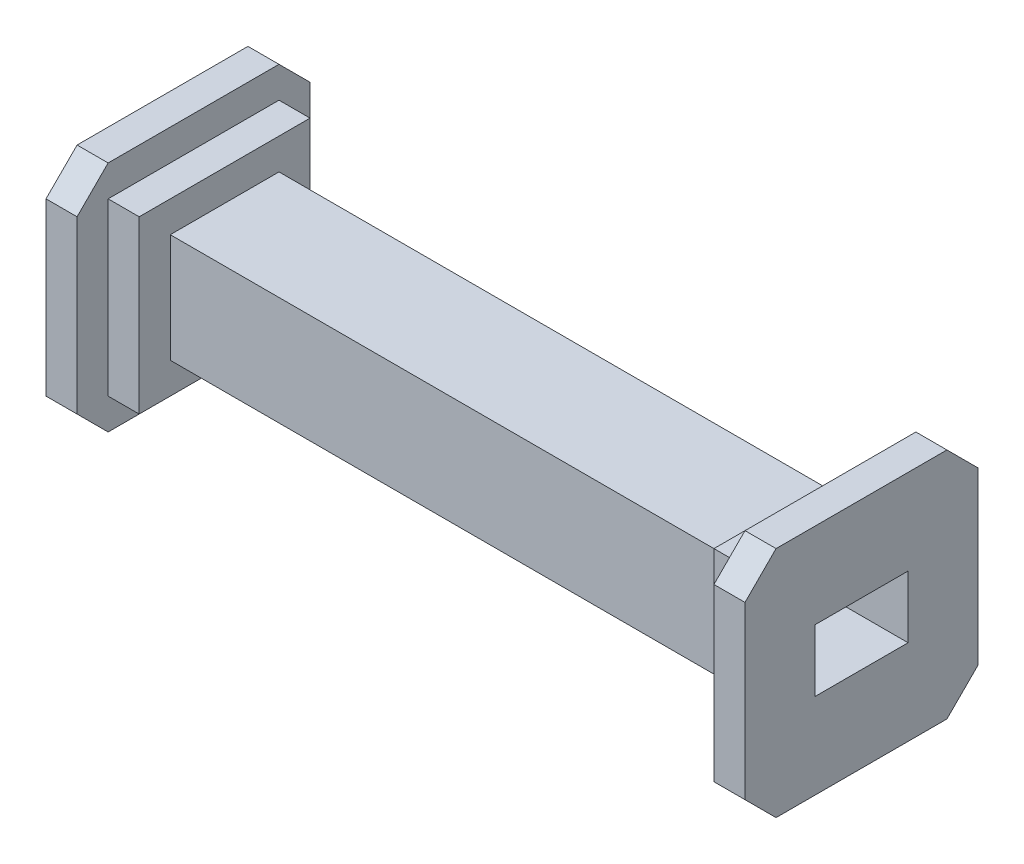
SolidWorks part; units mm, degrees
ref_plane "Front Plane" through (0, 0, 0) normal (0, 0, 1) x (1, 0, 0)
ref_plane "Top Plane" through (0, 0, 0) normal (0, 1, 0) x (1, 0, 0)
ref_plane "Right Plane" through (0, 0, 0) normal (1, 0, 0) x (0, 0, -1)
sketch "Sketch1" plane through (0, 0, 0) normal (1, 0, 0) x (0, 0, -1)
  line L1 (-19.05, -19.05) -> (19.05, -19.05)
  line L2 (-19.05, -19.05) -> (-19.05, 19.05)
  line L3 (-19.05, 19.05) -> (19.05, 19.05)
  line L4 (19.05, -19.05) -> (19.05, 19.05)
  line L5 (-19.05, -19.05) -> (19.05, 19.05) construction
  line L6 (-19.05, 19.05) -> (19.05, -19.05) construction
  point P0 (0, 0)
  dimension "D1" = 38.1
extrude "Boss-Extrude1" add sketch "Sketch1" along normal blind 114.3
sketch "Sketch3" plane through (0, 0, 0) normal (-1, 0, 0) x (0, 0, 1)
  line L8 (-13.97, 13.97) -> (-13.97, -13.97)
  line L9 (-13.97, -13.97) -> (13.97, -13.97)
  line L10 (13.97, -13.97) -> (13.97, 13.97)
  line L11 (13.97, 13.97) -> (-13.97, 13.97)
  line L12 (-13.97, 13.97) -> (-13.97, -13.97)
  line L13 (-13.97, -13.97) -> (13.97, -13.97)
  line L14 (13.97, -13.97) -> (13.97, 13.97)
  line L15 (13.97, 13.97) -> (-13.97, 13.97)
  line L16 (-19.05, 19.05) -> (-19.05, -19.05)
  line L17 (-19.05, -19.05) -> (19.05, -19.05)
  line L18 (19.05, -19.05) -> (19.05, 19.05)
  line L19 (19.05, 19.05) -> (-19.05, 19.05)
  line L20 (-19.05, 19.05) -> (-19.05, -19.05)
  line L21 (-19.05, -19.05) -> (19.05, -19.05)
  line L22 (19.05, -19.05) -> (19.05, 19.05)
  line L23 (19.05, 19.05) -> (-19.05, 19.05)
  dimension "D1" = 5.08
  dimension "D2" = 0
ref_plane "Plane1" through (5.08, 0, 0) normal (-1, 0, 0) x (0, 0, 1)
ref_plane "Plane2" through (10.16, 0, 0) normal (-1, 0, 0) x (0, 0, 1)
extrude "Cut-Extrude1" cut sketch "Sketch3" against normal blind 104.14 from surface at -5.08 starting at plane "Plane1"
ref_plane "Plane3" through (104.14, 0, 0) normal (-1, 0, 0) x (0, 0, 1)
sketch "Sketch4" plane through (10.16, 0, 0) normal (-1, 0, 0) x (0, 0, 1)
  line L4 (-19.05, 19.05) -> (-19.05, -19.05)
  line L5 (-19.05, -19.05) -> (19.05, -19.05)
  line L6 (19.05, -19.05) -> (19.05, 19.05)
  line L7 (19.05, 19.05) -> (-19.05, 19.05)
  line L8 (-19.05, 19.05) -> (-19.05, -19.05)
  line L9 (-19.05, -19.05) -> (19.05, -19.05)
  line L10 (19.05, -19.05) -> (19.05, 19.05)
  line L11 (19.05, 19.05) -> (-19.05, 19.05)
  line L16 (-8.89, 8.89) -> (-8.89, -8.89)
  line L17 (-8.89, -8.89) -> (8.89, -8.89)
  line L18 (8.89, -8.89) -> (8.89, 8.89)
  line L19 (8.89, 8.89) -> (-8.89, 8.89)
  line L20 (-8.89, 8.89) -> (-8.89, -8.89)
  line L21 (-8.89, -8.89) -> (8.89, -8.89)
  line L22 (8.89, -8.89) -> (8.89, 8.89)
  line L23 (8.89, 8.89) -> (-8.89, 8.89)
  dimension "D1" = 0
  dimension "D2" = 10.16
extrude "Cut-Extrude2" cut sketch "Sketch4" against normal up to surface (93.98 mm away)
sketch "Sketch5" plane through (0, 0, 0) normal (-1, 0, 0) x (0, 0, 1)
  line L0 (-19.05, 0) -> (19.05, 0) construction
  line L1 (-19.05, -19.05) -> (-19.05, 19.05) construction
  line L2 (19.05, 19.05) -> (19.05, -19.05) construction
  line L4 (-7.62, -5.08) -> (7.62, -5.08)
  line L5 (-7.62, -5.08) -> (-7.62, 5.08)
  line L6 (-7.62, 5.08) -> (7.62, 5.08)
  line L7 (7.62, -5.08) -> (7.62, 5.08)
  line L8 (-7.62, -5.08) -> (7.62, 5.08) construction
  line L9 (-7.62, 5.08) -> (7.62, -5.08) construction
  point P6 (0, 0)
  dimension "D1" = 10.16
  dimension "D2" = 15.24
extrude "Cut-Extrude3" cut sketch "Sketch5" against normal through all
chamfer "Chamfer1" distance 5.08 angle 45 8 edges at (111.76, -19.05, 19.05) (111.76, 19.05, 19.05) (111.76, 19.05, -19.05) (111.76, -19.05, -19.05) (2.54, -19.05, -19.05) (2.54, -19.05, 19.05) (2.54, 19.05, -19.05) (2.54, 19.05, 19.05)
